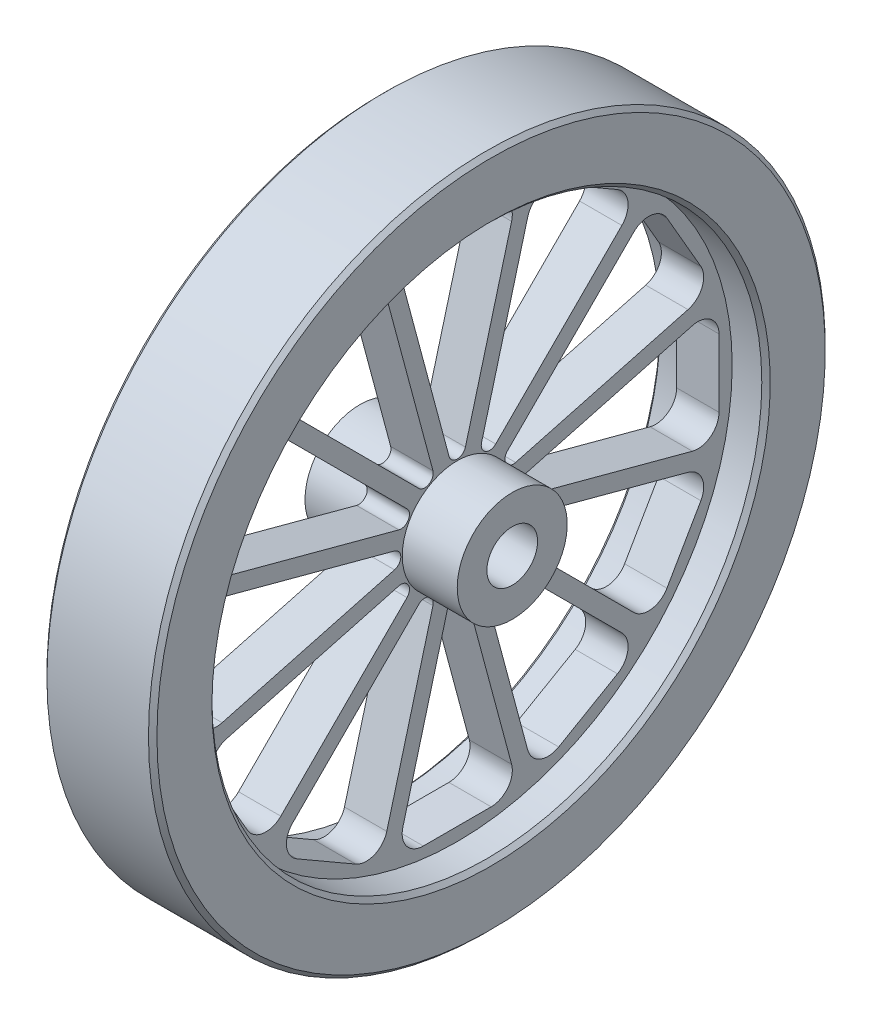
SolidWorks part; units mm, degrees
ref_plane "Front Plane" through (0, 0, 0) normal (0, 0, 1) x (1, 0, 0)
ref_plane "Top Plane" through (0, 0, 0) normal (0, 1, 0) x (1, 0, 0)
ref_plane "Right Plane" through (0, 0, 0) normal (1, 0, 0) x (0, 0, -1)
sketch "Sketch1" plane through (0, 0, 0) normal (0, 0, 1) x (1, 0, 0)
  line L0 (0, 0) -> (0, 20938.6642) construction
  line L1 (0, 0) -> (20938.6642, 0) construction
  line L2 (-18, 6) -> (18, 6)
  line L3 (18, 6) -> (18, 13)
  line L4 (18, 13) -> (5, 13)
  line L5 (5, 13) -> (5, 65)
  line L6 (5, 65) -> (13, 65)
  line L7 (13, 65) -> (13, 80)
  line L8 (13, 80) -> (-13, 80)
  line L9 (-13, 80) -> (-13, 65)
  line L10 (-13, 65) -> (-5, 65)
  line L11 (-5, 65) -> (-5, 13)
  line L12 (-5, 13) -> (-18, 13)
  line L13 (-18, 13) -> (-18, 6)
  point P7 (0, 80)
  point P18 (0, 6)
  dimension "D1" = 6
  dimension "D2" = 13
  dimension "D3" = 13
  dimension "D4" = 65
  dimension "D5" = 65
  dimension "D6" = 80
  dimension "D7" = 0
  dimension "D8" = 0
  dimension "D9" = 5
  dimension "D10" = 5
  dimension "D11" = 36
  dimension "D12" = 26
revolve "Revolve1" add sketch "Sketch1" angle 360 about L1
sketch "Sketch2" plane through (-5, 0, 0) normal (-1, 0, 0) x (0, 0, 1)
  line L0 (0, 0) -> (0, 50000) construction
  line L1 (0, 0) -> (50000, 0) construction
  line L2 (-8.0226, 61.8749) -> (8.0226, 61.8749)
  line L3 (12.8522, 55.5808) -> (1.9319, 14.8255)
  line L4 (-1.9319, 14.8255) -> (-12.8522, 55.5808)
  line L5 (23.9897, 57.5965) -> (37.8852, 49.5739)
  line L6 (5.7397, 13.8052) -> (16.6601, 54.5605)
  line L7 (38.9207, 41.7083) -> (9.0858, 11.8733)
  line L8 (49.5739, 37.8852) -> (57.5965, 23.9897)
  line L9 (11.8733, 9.0858) -> (41.7083, 38.9207)
  line L10 (54.5605, 16.6601) -> (13.8052, 5.7397)
  line L11 (61.8749, 8.0226) -> (61.8749, -8.0226)
  line L12 (14.8255, 1.9319) -> (55.5808, 12.8522)
  line L13 (55.5808, -12.8522) -> (14.8255, -1.9319)
  line L14 (57.5965, -23.9897) -> (49.5739, -37.8852)
  line L15 (13.8052, -5.7397) -> (54.5605, -16.6601)
  line L16 (41.7083, -38.9207) -> (11.8733, -9.0858)
  line L17 (37.8852, -49.5739) -> (23.9897, -57.5965)
  line L18 (9.0858, -11.8733) -> (38.9207, -41.7083)
  line L19 (16.6601, -54.5605) -> (5.7397, -13.8052)
  line L20 (8.0226, -61.8749) -> (-8.0226, -61.8749)
  line L21 (1.9319, -14.8255) -> (12.8522, -55.5808)
  line L22 (-12.8522, -55.5808) -> (-1.9319, -14.8255)
  line L23 (-23.9897, -57.5965) -> (-37.8852, -49.5739)
  line L24 (-5.7397, -13.8052) -> (-16.6601, -54.5605)
  line L25 (-38.9207, -41.7083) -> (-9.0858, -11.8733)
  line L26 (-49.5739, -37.8852) -> (-57.5965, -23.9897)
  line L27 (-11.8733, -9.0858) -> (-41.7083, -38.9207)
  line L28 (-54.5605, -16.6601) -> (-13.8052, -5.7397)
  line L29 (-61.8749, -8.0226) -> (-61.8749, 8.0226)
  line L30 (-14.8255, -1.9319) -> (-55.5808, -12.8522)
  line L31 (-55.5808, 12.8522) -> (-14.8255, 1.9319)
  line L32 (-57.5965, 23.9897) -> (-49.5739, 37.8852)
  line L33 (-13.8052, 5.7397) -> (-54.5605, 16.6601)
  line L34 (-41.7083, 38.9207) -> (-11.8733, 9.0858)
  line L35 (-37.8852, 49.5739) -> (-23.9897, 57.5965)
  line L36 (-9.0858, 11.8733) -> (-38.9207, 41.7083)
  line L37 (-16.6601, 54.5605) -> (-5.7397, 13.8052)
  arc A0 (37.8852, 49.5739) -> (38.9207, 41.7083) centre (35.3852, 45.2438) cw
  arc A1 (1.9319, 14.8255) -> (-1.9319, 14.8255) centre (0, 15.3431) cw
  arc A2 (8.0226, 61.8749) -> (12.8522, 55.5808) centre (8.0226, 56.8749) cw
  arc A3 (-8.0226, 61.8749) -> (-12.8522, 55.5808) centre (-8.0226, 56.8749) ccw
  arc A4 (23.9897, 57.5965) -> (16.6601, 54.5605) centre (21.4897, 53.2664) ccw
  arc A5 (9.0858, 11.8733) -> (5.7397, 13.8052) centre (7.6716, 13.2875) cw
  arc A6 (57.5965, 23.9897) -> (54.5605, 16.6601) centre (53.2664, 21.4897) cw
  arc A7 (49.5739, 37.8852) -> (41.7083, 38.9207) centre (45.2438, 35.3852) ccw
  arc A8 (13.8052, 5.7397) -> (11.8733, 9.0858) centre (13.2875, 7.6716) cw
  arc A9 (61.8749, -8.0226) -> (55.5808, -12.8522) centre (56.8749, -8.0226) cw
  arc A10 (61.8749, 8.0226) -> (55.5808, 12.8522) centre (56.8749, 8.0226) ccw
  arc A11 (14.8255, -1.9319) -> (14.8255, 1.9319) centre (15.3431, 0) cw
  arc A12 (49.5739, -37.8852) -> (41.7083, -38.9207) centre (45.2438, -35.3852) cw
  arc A13 (57.5965, -23.9897) -> (54.5605, -16.6601) centre (53.2664, -21.4897) ccw
  arc A14 (11.8733, -9.0858) -> (13.8052, -5.7397) centre (13.2875, -7.6716) cw
  arc A15 (23.9897, -57.5965) -> (16.6601, -54.5605) centre (21.4897, -53.2664) cw
  arc A16 (37.8852, -49.5739) -> (38.9207, -41.7083) centre (35.3852, -45.2438) ccw
  arc A17 (5.7397, -13.8052) -> (9.0858, -11.8733) centre (7.6716, -13.2875) cw
  arc A18 (-8.0226, -61.8749) -> (-12.8522, -55.5808) centre (-8.0226, -56.8749) cw
  arc A19 (8.0226, -61.8749) -> (12.8522, -55.5808) centre (8.0226, -56.8749) ccw
  arc A20 (-1.9319, -14.8255) -> (1.9319, -14.8255) centre (0, -15.3431) cw
  arc A21 (-37.8852, -49.5739) -> (-38.9207, -41.7083) centre (-35.3852, -45.2438) cw
  arc A22 (-23.9897, -57.5965) -> (-16.6601, -54.5605) centre (-21.4897, -53.2664) ccw
  arc A23 (-9.0858, -11.8733) -> (-5.7397, -13.8052) centre (-7.6716, -13.2875) cw
  arc A24 (-57.5965, -23.9897) -> (-54.5605, -16.6601) centre (-53.2664, -21.4897) cw
  arc A25 (-49.5739, -37.8852) -> (-41.7083, -38.9207) centre (-45.2438, -35.3852) ccw
  arc A26 (-13.8052, -5.7397) -> (-11.8733, -9.0858) centre (-13.2875, -7.6716) cw
  arc A27 (-61.8749, 8.0226) -> (-55.5808, 12.8522) centre (-56.8749, 8.0226) cw
  arc A28 (-61.8749, -8.0226) -> (-55.5808, -12.8522) centre (-56.8749, -8.0226) ccw
  arc A29 (-14.8255, 1.9319) -> (-14.8255, -1.9319) centre (-15.3431, 0) cw
  arc A30 (-49.5739, 37.8852) -> (-41.7083, 38.9207) centre (-45.2438, 35.3852) cw
  arc A31 (-57.5965, 23.9897) -> (-54.5605, 16.6601) centre (-53.2664, 21.4897) ccw
  arc A32 (-11.8733, 9.0858) -> (-13.8052, 5.7397) centre (-13.2875, 7.6716) cw
  arc A33 (-23.9897, 57.5965) -> (-16.6601, 54.5605) centre (-21.4897, 53.2664) cw
  arc A34 (-37.8852, 49.5739) -> (-38.9207, 41.7083) centre (-35.3852, 45.2438) ccw
  arc A35 (-5.7397, 13.8052) -> (-9.0858, 11.8733) centre (-7.6716, 13.2875) cw
  point P12 (0, 61.8749)
  point P18 (0, 7.6157)
  point P118 (0, 0)
  dimension "D2" = 2
  dimension "D3" = 5
  dimension "D1" = 30
  dimension "D4" = 12
extrude "Cut-Extrude1" cut sketch "Sketch2" against normal blind 20
chamfer "Chamfer1" distance 1 angle 45 4 edges at (-13, 0, 80) (13, 0, 80) (13, 0, 65) (-13, 0, 65)
